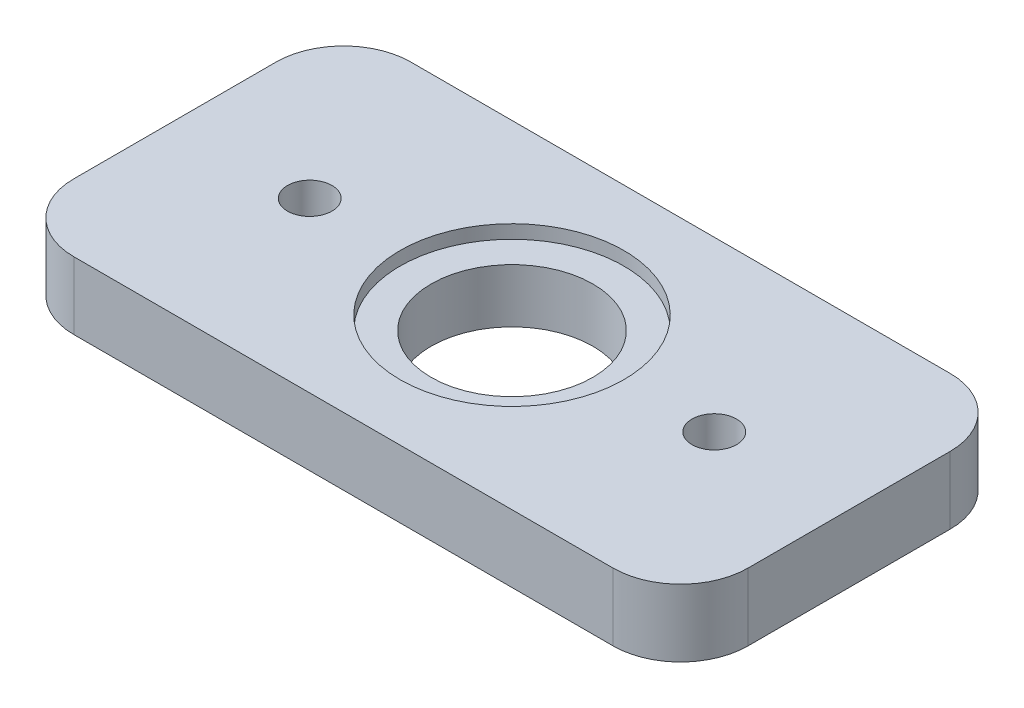
SolidWorks part; units mm, degrees
material "ABS"
ref_plane "前视基准面" through (0, 0, 0) normal (0, 0, 1) x (1, 0, 0)
ref_plane "上视基准面" through (0, 0, 0) normal (0, 1, 0) x (1, 0, 0)
ref_plane "右视基准面" through (0, 0, 0) normal (1, 0, 0) x (0, 0, -1)
sketch "草图1" plane through (0, 0, 0) normal (0, 1, 0) x (1, 0, 0)
  line L1 (0, 0) -> (50, 0)
  line L2 (0, 0) -> (0, 25)
  line L3 (0, 25) -> (50, 25)
  line L4 (50, 0) -> (50, 25)
  dimension "D1" = 50
  dimension "D2" = 25
extrude "凸台-拉伸1" add sketch "草图1" along normal blind 5
sketch "草图2" plane through (0, 5, 0) normal (0, 1, 0) x (1, 0, 0)
  line L0 (0, 12.5) -> (50, 12.5) construction
  line L1 (0, 25) -> (0, 0) construction
  line L2 (50, 0) -> (50, 25) construction
  line L3 (25, 25) -> (25, 0) construction
  line L4 (50, 25) -> (0, 25) construction
  line L5 (0, 0) -> (50, 0) construction
  circle A0 centre (25, 12.5) radius 6
  circle A1 centre (40, 12.5) radius 1.65
  circle A2 centre (10, 12.5) radius 1.65
  point P12 (25, 12.5)
  dimension "D1" = 12
  dimension "D2" = 3.3
  dimension "D3" = 30
extrude "切除-拉伸1" cut sketch "草图2" against normal blind 5
sketch "草图4" plane through (0, 5, 0) normal (0, 1, 0) x (1, 0, 0)
  circle A0 centre (25, 12.5) radius 8.3
  dimension "D1" = 16.6
extrude "切除-拉伸2" cut sketch "草图4" against normal blind 1
fillet "圆角1" radius 5 4 edges at (0, 2.5, -25) (0, 2.5, 0) (50, 2.5, 0) (50, 2.5, -25)
